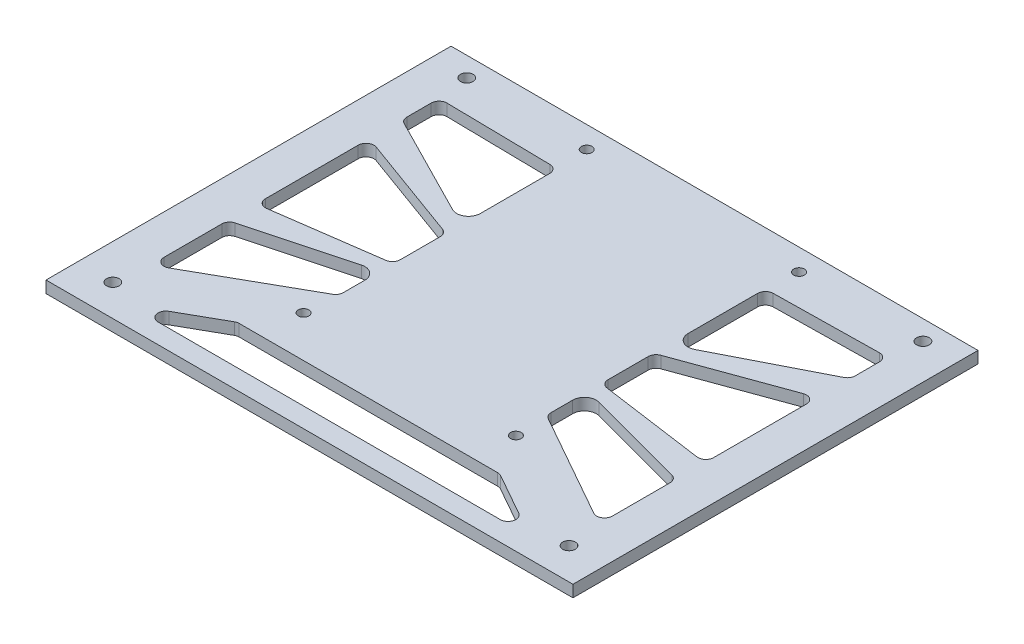
SolidWorks part; units mm, degrees
material "环氧树脂FR-4"
ref_plane "前视基准面" through (0, 0, 0) normal (0, 0, 1) x (1, 0, 0)
ref_plane "上视基准面" through (0, 0, 0) normal (0, 1, 0) x (1, 0, 0)
ref_plane "右视基准面" through (0, 0, 0) normal (1, 0, 0) x (0, 0, -1)
sketch "草图1" plane through (0, 0, 0) normal (0, 1, 0) x (1, 0, 0)
  line L1 (67, -51.5) -> (-67, -51.5)
  line L2 (67, -51.5) -> (67, 51.5)
  line L3 (67, 51.5) -> (-67, 51.5)
  line L4 (-67, -51.5) -> (-67, 51.5)
  line L5 (67, -51.5) -> (-67, 51.5) construction
  line L6 (67, 51.5) -> (-67, -51.5) construction
  point P0 (0, 0)
  dimension "D1" = 134
  dimension "D2" = 103
extrude "凸台-拉伸1" add sketch "草图1" along normal blind 3
sketch "草图2" plane through (0, 3, 0) normal (0, 1, 0) x (1, 0, 0)
  line L0 (0, 51.5) -> (0, 0) construction
  line L1 (67, 51.5) -> (-67, 51.5) construction
  line L2 (0, 11.8) -> (-10, 11.8) construction
  circle A0 centre (-10, 43.5) radius 1.6
  circle A1 centre (10, 43.5) radius 1.6
  circle A2 centre (0, 11.8) radius 1.6
  circle A3 centre (-10, 11.8) radius 1.6
  circle A4 centre (10, 11.8) radius 1.6
  dimension "D1" = 3.2
  dimension "D2" = 20
  dimension "D3" = 8
  dimension "D4" = 31.7
extrude "切除-拉伸1" [suppressed] cut sketch "草图2" against normal through all
pattern_linear "阵列(线性)1" [suppressed] count 3 spacing 10
sketch "草图4" [suppressed] plane through (0, 3, 0) normal (0, 1, 0) x (1, 0, 0)
  line L1 (35, 32.8) -> (-35, 32.8) construction
  line L2 (35, 32.8) -> (35, -22.2) construction
  line L3 (35, -22.2) -> (-35, -22.2) construction
  line L4 (-35, 32.8) -> (-35, -22.2) construction
  line L5 (35, 32.8) -> (-35, -22.2) construction
  line L6 (35, -22.2) -> (-35, 32.8) construction
  circle A0 centre (-35, -22.2) radius 1.6
  circle A1 centre (35, -22.2) radius 1.6
  circle A2 centre (35, 32.8) radius 1.6
  circle A3 centre (-35, 32.8) radius 1.6
  point P2 (0, 5.3)
  dimension "D3" = 3.2
  dimension "55" = 55
  dimension "D2" = 70
extrude "切除-拉伸2" [suppressed] cut sketch "草图4" against normal through all
sketch "草图5" plane through (0, 3, 0) normal (0, 1, 0) x (1, 0, 0)
  line L0 (0, 0) -> (0, 51.5) construction
  line L1 (67, 51.5) -> (-67, 51.5) construction
  line L3 (-27, 46) -> (27, 46) construction
  line L4 (-27, 46) -> (-27, -26) construction
  line L5 (-27, -26) -> (27, -26) construction
  line L6 (27, 46) -> (27, -26) construction
  line L7 (-27, 46) -> (27, -26) construction
  line L8 (-27, -26) -> (27, 46) construction
  circle A0 centre (27, -26) radius 1.35
  circle A1 centre (-27, -26) radius 1.35
  circle A2 centre (27, 46) radius 1.35
  circle A3 centre (-27, 46) radius 1.35
  point P6 (0, 10)
  dimension "D4" = 2.7
  dimension "D1" = 54
  dimension "D2" = 72
  dimension "D3" = 10
extrude "切除-拉伸3" cut sketch "草图5" against normal through all
sketch "草图6" plane through (0, 3, 0) normal (0, 1, 0) x (1, 0, 0)
  line L0 (67, -51.5) -> (67, 51.5) construction
  line L2 (67, 51.5) -> (-67, 51.5) construction
  line L3 (0, 0) -> (0, 51.5) construction
  circle A0 centre (58, 46.5) radius 1.6
  circle A1 centre (58, -43.5) radius 1.6
  circle A2 centre (-58, 46.5) radius 1.6
  circle A3 centre (-58, -43.5) radius 1.6
  dimension "D1" = 9
  dimension "D3" = 3.2
  dimension "D2" = 5
  dimension "D4" = 90
extrude "切除-拉伸4" cut sketch "草图6" against normal through all
sketch "草图7" plane through (0, 0, 0) normal (0, -1, 0) x (1, 0, 0)
  line L0 (-58, 43.5) -> (-27, 26) construction
  line L1 (-57, 34.8971) -> (-26.4207, 17.6346)
  line L2 (-26.4207, 17.6346) -> (-26.4207, -37.9896)
  line L3 (-27, -46) -> (-58, -46.5) construction
  line L4 (-26.4207, -37.9896) -> (-57, -38.4828)
  line L5 (-57, -38.4828) -> (-57, 34.8971)
  line L6 (-67, -51.5) -> (-67, 51.5) construction
  line L7 (0, 0) -> (0, -51.5) construction
  line L8 (67, -51.5) -> (-67, -51.5) construction
  line L9 (26.4207, -37.9896) -> (57, -38.4828)
  line L10 (26.4207, 17.6346) -> (26.4207, -37.9896)
  line L11 (57, 34.8971) -> (26.4207, 17.6346)
  line L12 (57, -38.4828) -> (57, 34.8971)
  line L13 (0, 0) -> (-57, 8.0108)
  line L14 (0, 0) -> (-57, -20.7463)
  line L16 (0, 0) -> (-57, 15.2731)
  line L17 (0, 0) -> (-57, -29.043)
  line L18 (0, 0) -> (57, -29.043)
  line L19 (0, 0) -> (57, -20.7463)
  line L20 (0, 0) -> (57, 8.0108)
  line L21 (0, 0) -> (57, 15.2731)
  dimension "D1" = 8
  dimension "D2" = 7
  dimension "D3" = 26.4207
  dimension "D4" = 10
  dimension "D5" = 82
  dimension "80" = 70
  dimension "D7" = 7
  dimension "D8" = 7
extrude "切除-拉伸5" cut sketch "草图7" against normal through all contours L16 L2 L1 L5 | L14 L2 L13 L5 | L2 L17 L5 L4 | L18 L10 L9 L12 | L20 L10 L19 L12 | L10 L21 L12 L11
fillet "圆角1" radius 3 4 edges at (26.4207, 1.5, 7.0794) (26.4207, 1.5, -13.462) (-26.4207, 1.5, -13.462) (-26.4207, 1.5, 7.0794)
sketch "草图9" plane through (0, 0, 0) normal (0, -1, 0) x (1, 0, 0)
  line L0 (58, 43.5) -> (27, 26) construction
  line L1 (0, 0) -> (0, 51.5) construction
  line L2 (-67, 51.5) -> (67, 51.5) construction
  line L3 (51.1091, 46.5) -> (33.3948, 36.5)
  line L4 (33.3948, 36.5) -> (-33.3948, 36.5)
  line L5 (51.1091, 46.5) -> (-51.1091, 46.5)
  line L6 (-51.1091, 46.5) -> (-33.3948, 36.5)
  point P14 (0, 46.5)
  point P15 (0, 36.5)
  dimension "D1" = 5
  dimension "D2" = 6
  dimension "D3" = 10
extrude "切除-拉伸6" cut sketch "草图9" against normal through all
fillet "圆角2" radius 2 24 edges at (-57, 1.5, -38.4828) (-57, 1.5, -29.043) (-26.4207, 1.5, -37.9896) (-26.4207, 1.5, 3.7132) (-26.4207, 1.5, -9.6163) (-57, 1.5, -20.7463) (57, 1.5, -20.7463) (26.4207, 1.5, -9.6163) (26.4207, 1.5, 3.7132) (57, 1.5, 8.0108) (57, 1.5, -38.4828) (26.4207, 1.5, -37.9896) (57, 1.5, -29.043) (-57, 1.5, 34.8971) (-26.4207, 1.5, 17.6346) (-57, 1.5, 15.2731) (26.4207, 1.5, 17.6346) (57, 1.5, 34.8971) (57, 1.5, 15.2731) (-57, 1.5, 8.0108) (33.3948, 1.5, 36.5) (-33.3948, 1.5, 36.5) (-51.1091, 1.5, 46.5) (51.1091, 1.5, 46.5)
